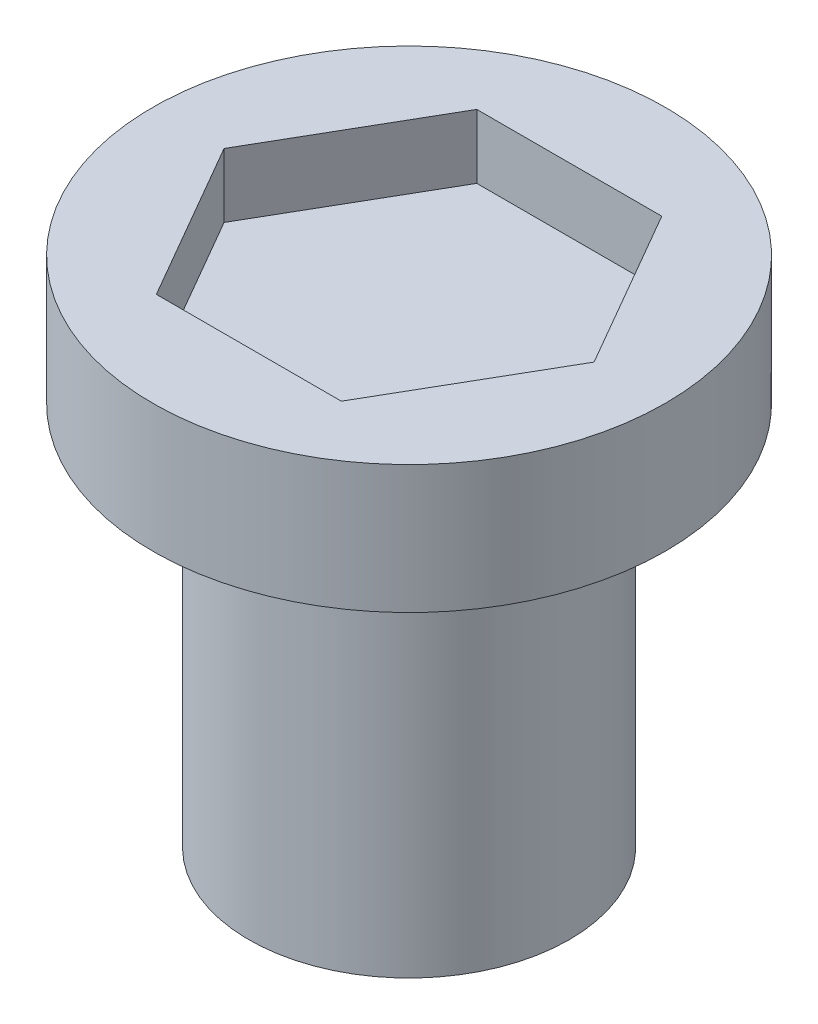
SolidWorks part; units mm, degrees
material "1060 Alloy"
ref_plane "Front Plane" through (0, 0, 0) normal (0, 0, 1) x (1, 0, 0)
ref_plane "Top Plane" through (0, 0, 0) normal (0, 1, 0) x (1, 0, 0)
ref_plane "Right Plane" through (0, 0, 0) normal (1, 0, 0) x (0, 0, -1)
sketch "Эскиз1" plane through (0, 0, 0) normal (0, 0, 1) x (1, 0, 0)
  line L0 (0, 0) -> (0, 4) construction
  line L1 (0, 0) -> (1.25, 0)
  line L2 (1.25, 0) -> (1.25, 3)
  line L3 (1.25, 3) -> (2, 3)
  line L4 (2, 3) -> (2, 4)
  line L5 (2, 4) -> (0, 4)
  line L6 (0, 4) -> (0, 0)
  line L7 (0, 4) -> (0, 5.6634) construction
  dimension "D1" = 2.5
  dimension "D2" = 3
  dimension "D3" = 4
  dimension "D4" = 1
revolve "Повернуть1" add sketch "Эскиз1" angle 360 about L7
sketch "Эскиз2" plane through (0, 4, 0) normal (0, 1, 0) x (1, 0, 0)
  line L1 (1.4434, 0) -> (0.7217, 1.25)
  line L2 (0.7217, 1.25) -> (-0.7217, 1.25)
  line L3 (-0.7217, 1.25) -> (-1.4434, 0)
  line L4 (-1.4434, 0) -> (-0.7217, -1.25)
  line L5 (-0.7217, -1.25) -> (0.7217, -1.25)
  line L6 (0.7217, -1.25) -> (1.4434, 0)
  circle A0 centre (0, 0) radius 1.25 construction
  point P1 (0, 0)
  dimension "D1" = 2.5
extrude "Вырез-Вытянуть1" cut sketch "Эскиз2" against normal blind 0.5
